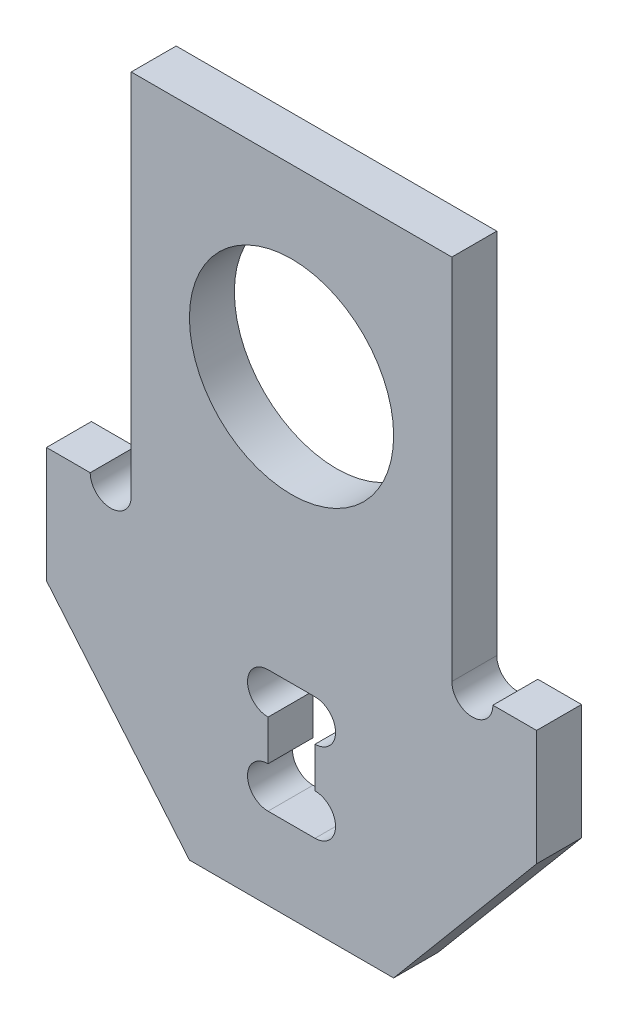
SolidWorks part; units mm, degrees
material "Thornel Mat VMA"
ref_plane "前视基准面" through (0, 0, 0) normal (0, 0, 1) x (1, 0, 0)
ref_plane "上视基准面" through (0, 0, 0) normal (0, 1, 0) x (1, 0, 0)
ref_plane "右视基准面" through (0, 0, 0) normal (1, 0, 0) x (0, 0, -1)
sketch "草图1" plane through (0, 0, 0) normal (0, 0, 1) x (1, 0, 0)
  line L0 (-7.85, -9) -> (-12, -9)
  line L1 (7.85, -9) -> (-7.85, -9) construction
  line L2 (7.85, -9) -> (7.85, 9)
  line L3 (7.85, 9) -> (-7.85, 9)
  line L4 (-7.85, -9) -> (-7.85, 9)
  line L5 (7.85, -9) -> (-7.85, 9) construction
  line L6 (7.85, 9) -> (-7.85, -9) construction
  line L7 (-12, -9) -> (-12, -23)
  line L8 (-12, -23) -> (12, -23)
  line L9 (0, 0) -> (0, -3.5592) construction
  line L10 (12, -9) -> (12, -23)
  line L11 (7.85, -9) -> (12, -9)
  line L21 (0, -16) -> (12, -16) construction
  line L22 (1.15, -19) -> (-1.15, -19)
  line L23 (1.15, -19) -> (1.15, -13)
  line L24 (1.15, -13) -> (-1.15, -13)
  line L25 (-1.15, -19) -> (-1.15, -13)
  line L26 (1.15, -19) -> (-1.15, -13) construction
  line L27 (1.15, -13) -> (-1.15, -19) construction
  line L28 (-12, -14.6577) -> (-5, -23)
  line L29 (12, -14.6577) -> (5, -23)
  circle A0 centre (8.855, -9) radius 1.005
  circle A1 centre (-8.855, -9) radius 1.005
  circle A2 centre (1.15, -14.005) radius 1.005
  circle A3 centre (-1.15, -14.005) radius 1.005
  circle A4 centre (-1.15, -17.995) radius 1.005
  circle A5 centre (1.15, -17.995) radius 1.005
  circle A6 centre (0, 0) radius 5
  point P0 (0, 0)
  point P22 (0, -16)
  dimension "D4" = 2.01
  dimension "D6" = 10
  dimension "D1" = 15.7
  dimension "D2" = 18
  dimension "D3" = 24
  dimension "D5" = 14
  dimension "D9" = 6
  dimension "D10" = 2.3
  dimension "D11" = 50
  dimension "D12" = 7
extrude "凸台-拉伸1" add sketch "草图1" along normal blind 2.2
